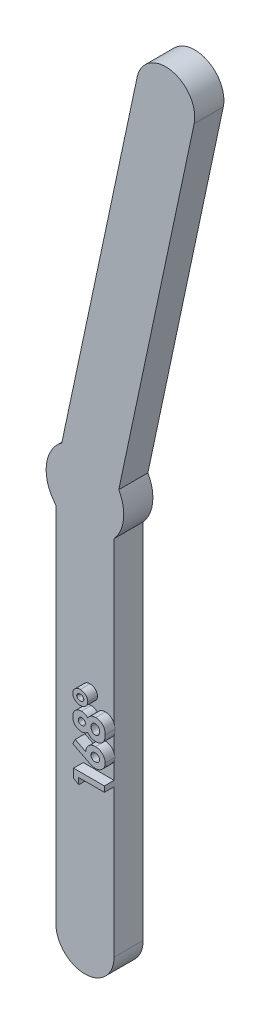
SolidWorks part; units mm, degrees
ref_plane "Front Plane" through (0, 0, 0) normal (0, 0, 1) x (1, 0, 0)
ref_plane "Top Plane" through (0, 0, 0) normal (0, 1, 0) x (1, 0, 0)
ref_plane "Right Plane" through (0, 0, 0) normal (1, 0, 0) x (0, 0, -1)
sketch "Sketch2" plane through (0, 0, 0) normal (0, 0, 1) x (1, 0, 0)
  line L0 (0, 0) -> (0, -40) construction
  line L1 (0, 0) -> (8.3165, 39.1259) construction
  line L2 (5.382, 39.7496) -> (11.2509, 38.5022) construction
  line L3 (-3, -40) -> (3, -40) construction
  line L4 (-3, -40) -> (-3, -2.6458)
  line L5 (3, -40) -> (3, -2.6458)
  line L6 (5.382, 39.7496) -> (-2.3844, 3.2117)
  line L7 (11.2509, 38.5022) -> (3.4845, 1.9642)
  arc A0 (-2.3844, 3.2117) -> (-3, -2.6458) centre (0, 0) ccw
  arc A1 (-3, -40) -> (3, -40) centre (0, -40) ccw
  arc A2 (5.382, 39.7496) -> (11.2509, 38.5022) centre (8.3165, 39.1259) cw
  arc A3 (3, -2.6458) -> (3.4845, 1.9642) centre (0, 0) ccw
  point P12 (8.3165, 39.1259)
  dimension "D3" = 3
  dimension "D4" = 8
  dimension "D1" = 40
  dimension "D2" = 168
extrude "Boss-Extrude1" add sketch "Sketch2" along normal blind 3
sketch "Sketch3" plane through (0, 0, 3) normal (0, 0, 1) x (1, 0, 0)
  text T0 "<b>168º</b>"
  point P1 (-20.3938, -5.2926)
  point P2 (0, 0)
  point P3 (0, 0)
extrude "Boss-Extrude2" add sketch "Sketch3" along normal blind 1
